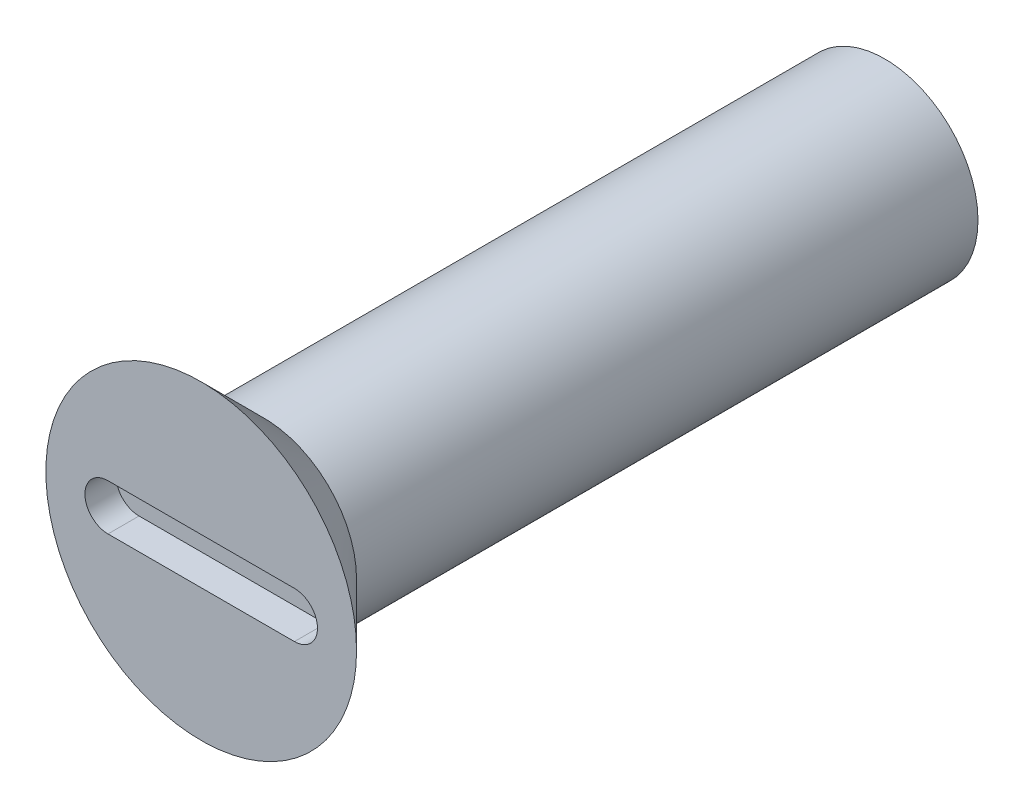
SolidWorks part; units mm, degrees
ref_plane "Front Plane" through (0, 0, 0) normal (0, 0, 1) x (1, 0, 0)
ref_plane "Top Plane" through (0, 0, 0) normal (0, 1, 0) x (1, 0, 0)
ref_plane "Right Plane" through (0, 0, 0) normal (1, 0, 0) x (0, 0, -1)
sketch "Sketch1" plane through (0, 0, 0) normal (0, 0, 1) x (1, 0, 0)
  circle A0 centre (0, 0) radius 1.5
extrude "Boss-Extrude1" add sketch "Sketch1" along normal blind 10
sketch "Sketch3" plane through (0, 0, 0) normal (0, 1, 0) x (1, 0, 0)
  line L0 (-1.5, -10) -> (-2.5, -11)
  line L1 (-2.5, -11) -> (0, -11)
  line L2 (0, -11) -> (0, -9.5024) construction
  line L3 (-1.5, -10) -> (0, -10)
  line L4 (-1.5, -10) -> (1.5, -10) construction
  line L5 (0, -11) -> (0, -10)
revolve "Revolve1" add sketch "Sketch3" angle 360 about L2
sketch "Sketch4" plane through (0, 0, 11) normal (0, 0, 1) x (1, 0, 0)
  line L0 (-1.5, 0) -> (1.5, 0) construction
  line L1 (-1.5, 0.3709) -> (1.5, 0.3709)
  line L2 (-1.5, -0.3709) -> (1.5, -0.3709)
  arc A0 (-1.5, 0.3709) -> (-1.5, -0.3709) centre (-1.5, 0) ccw
  arc A1 (1.5, -0.3709) -> (1.5, 0.3709) centre (1.5, 0) ccw
  point P0 (-1.5, 0)
  point P1 (0, 0)
  point P2 (1.5, 0)
extrude "Cut-Extrude1" cut sketch "Sketch4" against normal blind 0.5
